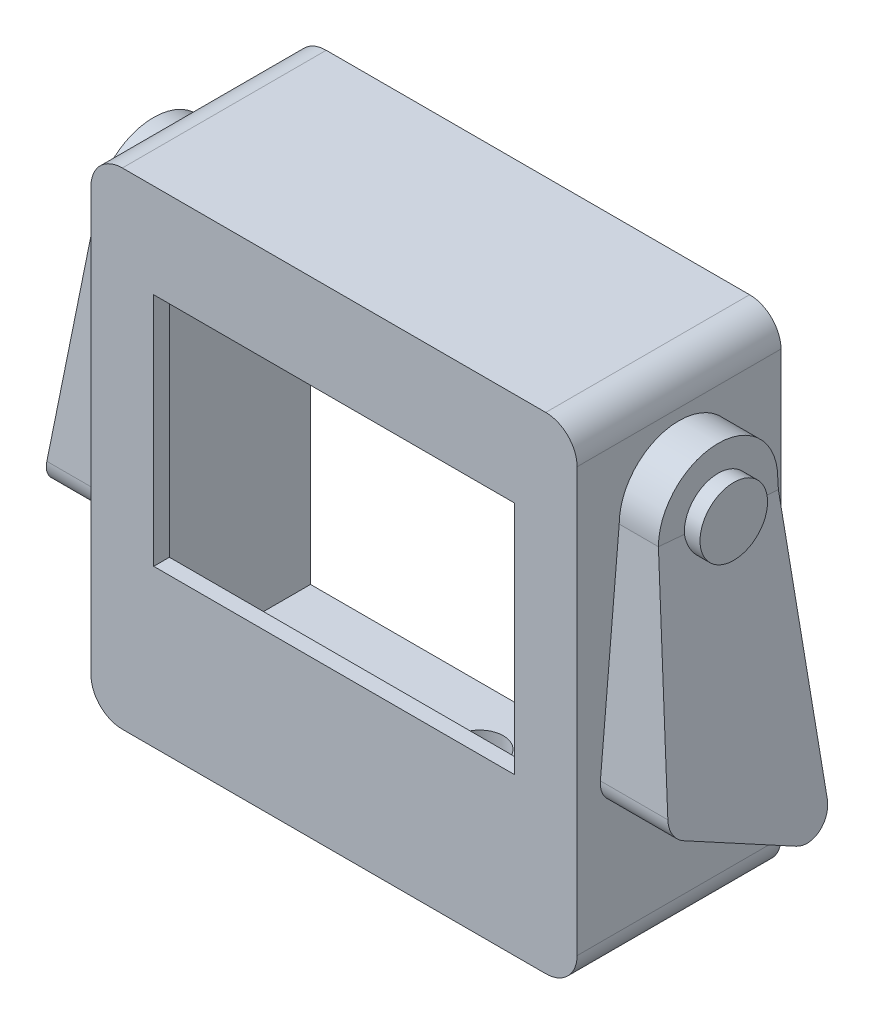
SolidWorks part; units mm, degrees
ref_plane "前视基准面" through (0, 0, 0) normal (0, 0, 1) x (1, 0, 0)
ref_plane "上视基准面" through (0, 0, 0) normal (0, 1, 0) x (1, 0, 0)
ref_plane "右视基准面" through (0, 0, 0) normal (1, 0, 0) x (0, 0, -1)
sketch "草图1" plane through (0, 0, 0) normal (0, 0, 1) x (1, 0, 0)
  line L1 (14.5, -14.5) -> (-14.5, -14.5)
  line L2 (14.5, -14.5) -> (14.5, 14.5)
  line L3 (14.5, 14.5) -> (-14.5, 14.5)
  line L4 (-14.5, -14.5) -> (-14.5, 14.5)
  line L10 (-11.5, 0) -> (-11.5, 9.5)
  line L11 (-11.5, 9.5) -> (11.5, 9.5)
  line L12 (11.5, 9.5) -> (11.5, -5.5)
  line L13 (11.5, -5.5) -> (-11.5, -5.5)
  line L14 (-11.5, -5.5) -> (-11.5, 0)
  point P0 (0, 0)
  dimension "D1" = 29
  dimension "D2" = 29
extrude "凸台-拉伸1" add sketch "草图1" along normal blind 1
sketch "草图2" plane through (0, 0, 1) normal (0, 0, 1) x (1, 0, 0)
  line L0 (15.5, -15.5) -> (15.5, 15.5)
  line L1 (14.5, -14.5) -> (-14.5, -14.5)
  line L2 (14.5, -14.5) -> (14.5, 14.5)
  line L3 (14.5, 14.5) -> (-14.5, 14.5)
  line L4 (-14.5, -14.5) -> (-14.5, 14.5)
  line L5 (15.5, 15.5) -> (-15.5, 15.5)
  line L6 (-15.5, -15.5) -> (-15.5, 15.5)
  line L7 (15.5, -15.5) -> (-15.5, -15.5)
  point P0 (0, 0)
  dimension "D1" = 1
extrude "凸台-拉伸2" add sketch "草图2" against normal blind 13
sketch "草图3" plane through (15.5, 0, 0) normal (1, 0, 0) x (0, 0, -1)
  line L0 (1.6841, 8.99) -> (0.3971, -5.5956)
  line L1 (0.3971, -5.5956) -> (10.4512, -10.7921)
  line L2 (10.4512, -10.7921) -> (9.2959, 8.99)
  arc A1 (9.2959, 8.99) -> (1.6841, 8.99) centre (5.49, 8.99) ccw
extrude "凸台-拉伸4" add sketch "草图3" along normal blind 5
sketch "草图4" plane through (0, -0.078, -0.884) normal (0, 0.0879, 0.9961) x (1, 0, 0)
  line L0 (18, 9.1032) -> (20.5, -9.8318)
  line L1 (20.5, 9.1032) -> (15.5, 9.1032) construction
  line L2 (18, 9.1032) -> (18, 13.2437)
  line L3 (20.5, 13.2437) -> (15.5, 13.2437) construction
  line L4 (18, 13.2437) -> (20.5, 13.2437)
  line L5 (20.5, 13.2437) -> (20.5, -9.8318)
extrude "切除-拉伸2" cut sketch "草图4" against normal blind 14 and the other way blind 13
sketch "草图5" plane through (18, 0, 0) normal (1, 0, 0) x (0, 0, -1)
  circle A0 centre (5.49, 8.99) radius 2.1537
extrude "凸台-拉伸5" add sketch "草图5" along normal blind 1
mirror "镜向1" about plane through (0, 0, 0) normal (1, 0, 0) of "凸台-拉伸4", "切除-拉伸2", "凸台-拉伸5"
fillet "圆角2" radius 2 4 edges at (15.5, -15.5, -5.5) (15.5, 15.5, -5.5) (-15.5, 15.5, -5.5) (-15.5, -15.5, -5.5)
fillet "圆角3" radius 1.5 4 edges at (18, -10.7921, -10.4512) (17.7166, -5.5956, -0.3971) (-18, -10.7921, -10.4512) (-17.7166, -5.5956, -0.3971)
sketch "草图6" plane through (0, -14.5, 0) normal (0, 1, 0) x (1, 0, 0)
  circle A0 centre (0, 8.2925) radius 1.5
  dimension "D1" = 3
extrude "切除-拉伸3" cut sketch "草图6" against normal blind 10
